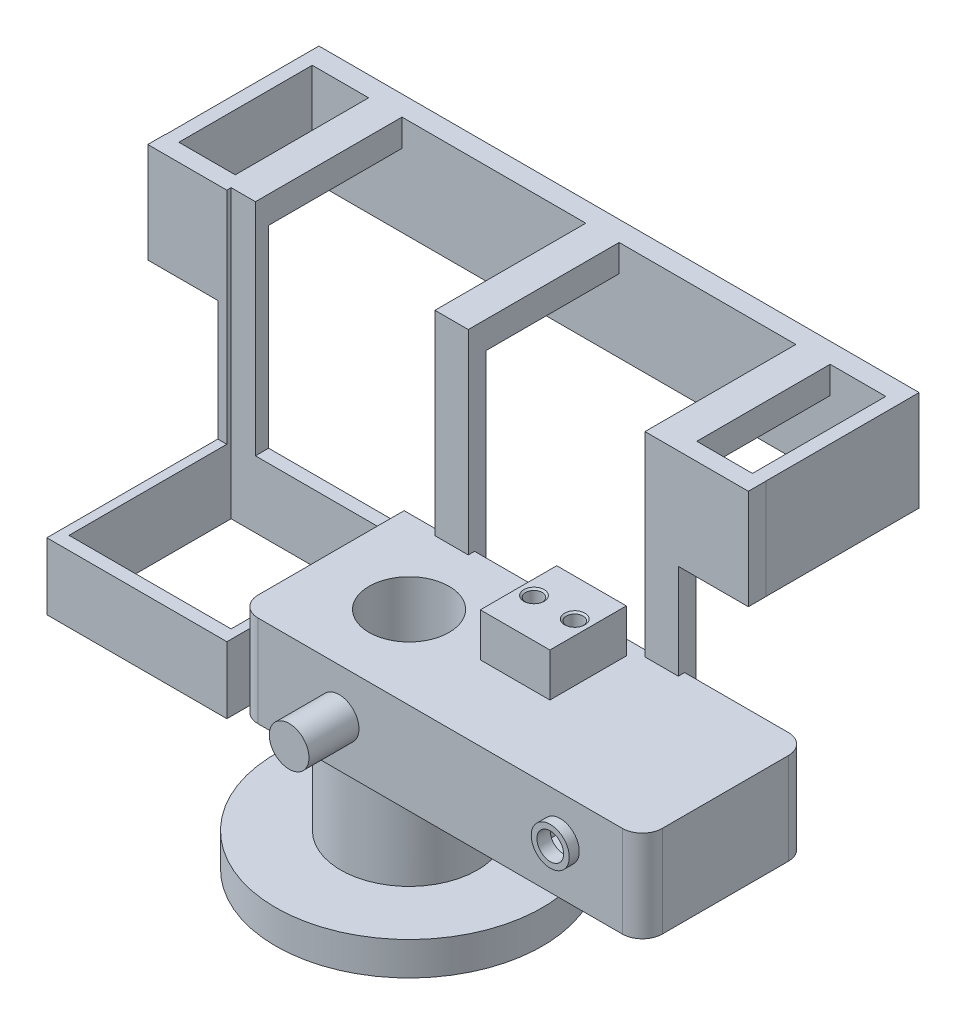
SolidWorks part; units mm, degrees
ref_plane "前基準面" through (0, 0, 0) normal (0, 0, 1) x (1, 0, 0)
ref_plane "上基準面" through (0, 0, 0) normal (0, 1, 0) x (1, 0, 0)
ref_plane "右基準面" through (0, 0, 0) normal (1, 0, 0) x (0, 0, -1)
sketch "草圖1" plane through (0, 0, 0) normal (0, 1, 0) x (1, 0, 0)
  line L1 (-30.3038, 12.448) -> (30.3038, 12.448)
  line L2 (-30.3038, 12.448) -> (-30.3038, -12.448)
  line L3 (-30.3038, -12.448) -> (30.3038, -12.448)
  line L4 (30.3038, 12.448) -> (30.3038, -12.448)
  line L5 (-30.3038, 12.448) -> (30.3038, -12.448) construction
  line L6 (-30.3038, -12.448) -> (30.3038, 12.448) construction
  point P0 (0, 0)
extrude "填料-伸長1" add sketch "草圖1" along normal blind 13.7304
sketch "草圖2" plane through (0, 0, 12.448) normal (0, 0, 1) x (1, 0, 0)
  line L6 (11.75, 12.75) -> (24.25, 12.75)
  line L7 (11.75, 12.75) -> (11.75, 2.25)
  line L8 (11.75, 2.25) -> (24.25, 2.25)
  line L9 (24.25, 12.75) -> (24.25, 2.25)
  line L10 (11.75, 12.75) -> (24.25, 2.25) construction
  line L11 (11.75, 2.25) -> (24.25, 12.75) construction
  point P10 (18, 7.5)
  dimension "D1" = 10.5
  dimension "D2" = 12.5
extrude "除料-伸長1" cut sketch "草圖2" against normal through all
sketch "草圖3" plane through (0, 0, 12.448) normal (0, 0, 1) x (1, 0, 0)
  line L0 (24.25, 2.25) -> (24.25, 12.75) construction
  line L1 (11.75, 12.75) -> (24.25, 12.75)
  line L2 (11.75, 12.75) -> (11.75, 2.25)
  line L3 (11.75, 2.25) -> (24.25, 2.25)
  line L4 (24.25, 12.75) -> (24.25, 2.25)
  line L5 (11.75, 12.75) -> (24.25, 2.25) construction
  line L6 (11.75, 2.25) -> (24.25, 12.75) construction
  line L7 (11.75, 2.25) -> (24.25, 2.25) construction
  point P0 (18, 7.5)
extrude "填料-伸長2" add sketch "草圖3" against normal blind 0.5
sketch "草圖4" plane through (0, 0, 11.948) normal (0, 0, -1) x (-1, 0, 0)
  circle A0 centre (-18, 7.5) radius 2
extrude "除料-伸長2" cut sketch "草圖4" against normal through all
sketch "草圖5" plane through (0, 0, 12.448) normal (0, 0, 1) x (1, 0, 0)
  circle A0 centre (-15.1519, 6.9) radius 2.975
extrude "填料-伸長3" add sketch "草圖5" along normal blind 7.5
sketch "草圖10" plane through (0, 13.7304, 0) normal (0, 1, 0) x (1, 0, 0)
  line L5 (-5.2158, 10.2392) -> (5.2158, 10.2392)
  line L6 (-5.2158, 10.2392) -> (-5.2158, -1.2175)
  line L7 (-5.2158, -1.2175) -> (5.2158, -1.2175)
  line L8 (5.2158, 10.2392) -> (5.2158, -1.2175)
  line L9 (-5.2158, 10.2392) -> (5.2158, -1.2175) construction
  line L10 (-5.2158, -1.2175) -> (5.2158, 10.2392) construction
  point P0 (0, 4.5109)
extrude "填料-伸長4" add sketch "草圖10" along normal blind 6.5
sketch "草圖14" plane through (0, 0, 12.448) normal (0, 0, 1) x (1, 0, 0)
  circle A0 centre (18, 7.5) radius 2.8505
  circle A1 centre (18, 7.5) radius 2
extrude "填料-伸長5" add sketch "草圖14" along normal blind 1.5
fillet "圓角2" radius 3 1 edges at (-30.3038, 6.8652, 12.448)
fillet "圓角3" radius 3 1 edges at (30.3038, 6.8652, -12.448)
fillet "圓角4" radius 3 1 edges at (30.3038, 6.8652, 12.448)
sketch "草圖16" plane through (0, 0, 0) normal (0, -1, 0) x (1, 0, 0)
  circle A0 centre (-17.1174, 0) radius 5.5
  circle A1 centre (-17.1174, 0) radius 7.5
extrude "填料-伸長6" add sketch "草圖16" along normal blind 15
sketch "草圖17" plane through (0, -15, 0) normal (0, -1, 0) x (1, 0, 0)
  circle A0 centre (-17.1174, 0) radius 9.15
  circle A1 centre (-17.1174, 0) radius 17.05
extrude "填料-伸長7" add sketch "草圖17" along normal blind 5 separate body
sketch "草圖18" plane through (0, -15, 0) normal (0, 1, 0) x (1, 0, 0)
  circle A0 centre (-17.1174, 0) radius 10.2514
extrude "填料-伸長8" add sketch "草圖18" along normal blind 15
sketch "草圖19" plane through (0, -15, 0) normal (0, -1, 0) x (1, 0, 0)
  circle A0 centre (-17.1174, 0) radius 6
extrude "除料-伸長3" cut sketch "草圖19" against normal through all
sketch "草圖20" plane through (0, -20, 0) normal (0, -1, 0) x (1, 0, 0)
  line L1 (-27.7874, 1.565) -> (-27.7874, -1.565)
  line L2 (-27.7874, 1.565) -> (-26.1326, 1.565)
  line L3 (-27.7874, -1.565) -> (-26.1326, -1.565)
  line L4 (-26.1326, 1.565) -> (-26.1326, -1.565)
  circle A0 centre (-17.1174, 0) radius 9.15 construction
  point P7 (-27.7874, 0)
extrude "除料-伸長4" cut sketch "草圖20" against normal blind 15
sketch "草圖21" plane through (0, -15, 0) normal (0, -1, 0) x (1, 0, 0)
  line L0 (-26.1326, 1.565) -> (-25.7373, 1.565)
  line L1 (-26.1326, -1.565) -> (-25.7373, -1.565)
  line L2 (-25.7373, -1.565) -> (-25.7373, 1.565)
  line L3 (-26.1326, 1.565) -> (-26.1326, -1.565)
extrude "除料-伸長5" cut sketch "草圖21" against normal blind 10
sketch "草圖22" plane through (0, -15, 0) normal (0, 1, 0) x (1, 0, 0)
  circle A0 centre (-17.1174, 0) radius 19.9648
extrude "除料-伸長6" cut sketch "草圖22" against normal blind 10
sketch "草圖47" plane through (0, -15, 0) normal (0, -1, 0) x (1, 0, 0)
  circle A0 centre (-17.1174, 0) radius 20
extrude "填料-伸長16" add sketch "草圖47" along normal blind 5
sketch "草圖48" plane through (0, -15, 0) normal (0, 1, 0) x (1, 0, 0)
  circle A0 centre (-17.1174, 0) radius 6
extrude "除料-伸長21" cut sketch "草圖48" against normal blind 5
sketch "草圖49" plane through (0, -20, 0) normal (0, -1, 0) x (1, 0, 0)
  circle A0 centre (-17.1174, 0) radius 17.3
  circle A1 centre (-17.1174, 0) radius 14.8
extrude "除料-伸長22" cut sketch "草圖49" against normal blind 3
sketch "草圖50" plane through (0, -20, 0) normal (0, -1, 0) x (1, 0, 0)
  circle A0 centre (-17.1174, 0) radius 18.5909
  arc A1 (-2.1064, 10.9677) -> (0.2479, 6.6384) centre (-17.1174, 0) cw
  circle A2 centre (-17.1174, 0) radius 8.4841
sketch "草圖51" plane through (0, -20, 0) normal (0, -1, 0) x (1, 0, 0)
  line L0 (-3.1487, 10.2061) -> (-2.1064, 10.9677)
  line L1 (-0.958, 6.1775) -> (0.2479, 6.6384)
  line L2 (-15.2631, -17.2003) -> (-15.1247, -18.4838)
  line L3 (-19.8473, -17.0833) -> (-20.051, -18.358)
  line L4 (-32.9405, 6.9942) -> (-34.1213, 7.5161)
  line L5 (-30.547, 10.9058) -> (-31.5491, 11.7196)
  arc A0 (-3.1487, 10.2061) -> (-0.958, 6.1775) centre (-17.1174, 0) cw
  circle A1 centre (-17.1174, 0) radius 17.3 construction
  arc A2 (-15.1247, -18.4838) -> (-20.051, -18.358) centre (-17.1174, 0) cw
  arc A3 (-2.1064, 10.9677) -> (0.2479, 6.6384) centre (-17.1174, 0) cw
  arc A4 (-15.2631, -17.2003) -> (-19.8473, -17.0833) centre (-17.1174, 0) cw
  arc A5 (-34.1213, 7.5161) -> (-31.5491, 11.7196) centre (-17.1174, 0) cw
  arc A6 (-32.9405, 6.9942) -> (-30.547, 10.9058) centre (-17.1174, 0) cw
  point P23 (-17.1174, 0)
  dimension "D1" = 3
extrude "除料-伸長23" cut sketch "草圖51" against normal blind 3
sketch "草圖52" plane through (0, -17, 0) normal (0, -1, 0) x (1, 0, 0)
  circle A0 centre (-17.1174, 0) radius 18.5909
extrude "除料-伸長24" cut sketch "草圖52" along normal blind 2.3
sketch "草圖43" plane through (0, 0, 0) normal (0, -1, 0) x (1, 0, 0)
  line L0 (-30.3038, 14.126) -> (-30.3038, -14.126)
  line L1 (-57.3038, -14.126) -> (-57.3038, 14.126)
  line L2 (-30.3038, -14.126) -> (-57.3038, -14.126)
  line L3 (-57.3038, 14.126) -> (-30.3038, 14.126)
  line L6 (-55.9538, 12.15) -> (-31.6538, 12.15)
  line L7 (-55.9538, 12.15) -> (-55.9538, -12.15)
  line L8 (-55.9538, -12.15) -> (-31.6538, -12.15)
  line L9 (-31.6538, 12.15) -> (-31.6538, -12.15)
  line L10 (-55.9538, 12.15) -> (-31.6538, -12.15) construction
  line L11 (-55.9538, -12.15) -> (-31.6538, 12.15) construction
  point P3 (-30.3038, 0)
  point P7 (-43.8038, 0)
  dimension "D1" = 27
  dimension "D2" = 24.3
  dimension "D3" = 24.3
extrude "填料-伸長14" add sketch "草圖43" against normal blind 10
sketch "草圖53" plane through (0, -20, 0) normal (0, -1, 0) x (1, 0, 0)
  line L0 (-21.4684, 18.0746) -> (-18.5217, 5.8334)
  line L1 (-12.8881, 18.1034) -> (-15.7525, 5.8427)
  line L2 (0.7111, -5.2692) -> (-11.3635, -1.7006)
  line L3 (-3.5541, -12.7145) -> (-12.74, -4.1034)
  line L4 (-30.595, -12.8054) -> (-21.4672, -4.1328)
  line L5 (-34.9102, -5.389) -> (-22.8598, -1.7392)
  circle A1 centre (-17.1174, 0) radius 18.5909 construction
  circle A2 centre (-17.1174, 0) radius 6 construction
  arc A3 (-15.7525, 5.8427) -> (-18.5217, 5.8334) centre (-17.1174, 0) ccw
  arc A4 (-21.4684, 18.0746) -> (-12.8881, 18.1034) centre (-17.1174, 0) cw
  arc A5 (0.7111, -5.2692) -> (-3.5541, -12.7145) centre (-17.1174, 0) cw
  arc A6 (-12.74, -4.1034) -> (-11.3635, -1.7006) centre (-17.1174, 0) ccw
  arc A7 (-30.595, -12.8054) -> (-34.9102, -5.389) centre (-17.1174, 0) cw
  arc A8 (-22.8598, -1.7392) -> (-21.4672, -4.1328) centre (-17.1174, 0) ccw
  point P20 (-17.1174, 0)
  dimension "D1" = 3
extrude "填料-伸長17" add sketch "草圖53" against normal blind 5
sketch "草圖54" plane through (0, -20, 0) normal (0, -1, 0) x (1, 0, 0)
  circle A0 centre (-17.1174, 0) radius 14.8
  circle A1 centre (-17.1174, 0) radius 6
extrude "填料-伸長18" add sketch "草圖54" against normal blind 5
sketch "草圖56" plane through (30.3038, 0, 0) normal (1, 0, 0) x (0, 0, -1)
  line L0 (14.126, 10) -> (14.126, 0)
  line L1 (14.126, 0) -> (12.448, 0)
  line L2 (12.448, 0) -> (12.448, 10)
  line L3 (14.126, 10) -> (12.448, 10) construction
  line L4 (12.448, 10) -> (14.126, 10)
extrude "填料-伸長19" add sketch "草圖56" against normal blind 80
sketch "草圖57" plane through (0, 0, -12.448) normal (0, 0, -1) x (-1, 0, 0)
  line L0 (-24.25, 12.75) -> (-11.75, 12.75)
  line L1 (-11.75, 12.75) -> (-11.75, 0.75)
  line L2 (-24.25, 12.75) -> (-24.25, 0.75)
  line L3 (-24.25, 0.75) -> (-11.75, 0.75)
extrude "除料-伸長28" cut sketch "草圖57" along normal blind 80
sketch "草圖58" plane through (30.3038, 0, 0) normal (1, 0, 0) x (0, 0, -1)
  line L0 (12.448, 10) -> (14.126, 10)
  line L1 (14.126, 10) -> (14.126, 0)
  line L2 (14.126, 0) -> (12.448, 0)
  line L3 (12.448, 0) -> (12.448, 10)
extrude "除料-伸長29" cut sketch "草圖58" against normal blind 18.5
sketch "草圖59" plane through (0, 0, -14.126) normal (0, 0, -1) x (-1, 0, 0)
  line L0 (-11.75, 10) -> (-11.75, 43)
  line L1 (-11.75, 10) -> (-6.75, 10)
  line L2 (57.3038, 10) -> (-11.75, 10) construction
  line L3 (-6.75, 10) -> (-6.75, 43)
  line L4 (-6.75, 43) -> (-11.75, 43)
  line L5 (57.3038, 10) -> (57.3038, 43)
  line L6 (57.3038, 43) -> (52.3038, 43)
  line L7 (52.3038, 43) -> (52.3038, 0)
  line L8 (57.3038, 0) -> (-11.8038, 0) construction
  line L9 (52.3038, 0) -> (57.3038, 0)
  line L10 (19.7432, 0) -> (19.7432, 43)
  line L11 (19.7432, 43) -> (24.7432, 43)
  line L12 (24.7432, 43) -> (24.7432, 0)
  line L13 (24.7432, 0) -> (19.7432, 0)
  line M14 (57.3038, 10) -> (-11.75, 10)
  dimension "D1" = 5
  dimension "D2" = 5
  dimension "D3" = 5
extrude "填料-伸長21" add sketch "草圖59" against normal blind 2.621 contours L3 L4 L0 M14 | L12 L11 L10 M14 | L6 L7 L5 M14
sketch "草圖60" plane through (-57.3038, 0, 0) normal (-1, 0, 0) x (0, 0, 1)
  line L0 (-14.126, 43) -> (-39.126, 43)
  line L1 (-39.126, 43) -> (-39.126, 38.9382)
  line L3 (-11.5051, 10) -> (-11.5051, 43) construction
  line L4 (-39.126, 38.9382) -> (-14.126, 38.9382)
  line L5 (-14.126, 38.9382) -> (-14.126, 43)
  line L10 (-14.126, 0) -> (14.126, 0)
  line L11 (14.126, 0) -> (14.126, 10)
  line L12 (14.126, 10) -> (-11.5051, 10)
  line L13 (-11.5051, 10) -> (-11.5051, 43)
  line L14 (-11.5051, 43) -> (-14.126, 43)
  line L15 (-14.126, 43) -> (-14.126, 0)
  line L16 (-14.126, 0) -> (14.126, 0)
  line L17 (14.126, 0) -> (14.126, 10)
  line L18 (14.126, 10) -> (-11.5051, 10)
  line L19 (-11.5051, 10) -> (-11.5051, 38.9382)
  line L21 (-14.126, 43) -> (-14.126, 0)
  line M12 (-14.126, 43) -> (-14.126, 0)
  dimension "D1" = 0
extrude "填料-伸長22" add sketch "草圖60" against normal blind 69.2 contours L1 L4 L0 M12
sketch "草圖61" plane through (0, 43, 0) normal (0, 1, 0) x (1, 0, 0)
  line L0 (6.75, 14.126) -> (6.75, 34.126)
  line L1 (-19.7432, 14.126) -> (-19.7432, 34.126)
  line L2 (-19.7432, 34.126) -> (6.75, 34.126)
  line L3 (-24.7432, 14.126) -> (-24.7432, 34.126)
  line L4 (-52.3038, 14.126) -> (-52.3038, 34.126)
  line L5 (-52.3038, 34.126) -> (-24.7432, 34.126)
  line L6 (-52.3038, 14.126) -> (-24.7432, 14.126)
  line L7 (-19.7432, 14.126) -> (6.75, 14.126)
extrude "除料-伸長30" cut sketch "草圖61" against normal blind 5.2
sketch "草圖62" plane through (0, 38.9382, 0) normal (0, -1, 0) x (1, 0, 0)
  line L0 (-57.3038, -39.126) -> (11.8962, -39.126)
  line L1 (-52.3038, -34.126) -> (11.8962, -34.126)
  line L2 (11.8962, -39.126) -> (11.8962, -14.126) construction
  line L3 (11.8962, -34.126) -> (11.8962, -39.126)
  line L4 (-57.3038, -39.126) -> (-57.3038, -34.126)
  line L5 (-57.3038, -39.126) -> (-57.3038, -14.126) construction
  line L6 (-57.3038, -34.126) -> (-52.3038, -34.126)
sketch "草圖68" plane through (0, 0, -34.126) normal (0, 0, 1) x (1, 0, 0)
  line L0 (-65.7613, 43) -> (20.2387, 43)
  line L2 (20.2387, 43) -> (20.2387, 28)
  line L3 (20.2387, 28) -> (-65.7613, 28)
  line L4 (-65.7613, 28) -> (-65.7613, 43)
  point P3 (-22.7613, 43)
  dimension "D1" = 86
extrude "填料-伸長25" add sketch "草圖68" against normal blind 3
sketch "草圖69" plane through (0, 0, -39.126) normal (0, 0, -1) x (-1, 0, 0)
  line L0 (-11.8962, 43) -> (-11.8962, 38.9382)
  line L1 (-11.8962, 38.9382) -> (57.3038, 38.9382)
  line L2 (57.3038, 38.9382) -> (57.3038, 43)
  line L3 (57.3038, 43) -> (-11.8962, 43)
extrude "除料-伸長34" cut sketch "草圖69" against normal blind 2
sketch "草圖70" plane through (20.2387, 0, 0) normal (1, 0, 0) x (0, 0, -1)
  line L0 (37.126, 28) -> (37.126, 43)
  line L1 (37.126, 43) -> (14.126, 43)
  line L2 (14.126, 43) -> (14.126, 28)
  line L3 (14.126, 38.9382) -> (14.126, 0.75) construction
  line L4 (14.126, 28) -> (37.126, 28)
extrude "填料-伸長27" add sketch "草圖70" along normal blind 2
sketch "草圖71" plane through (-65.7613, 0, 0) normal (-1, 0, 0) x (0, 0, 1)
  line L0 (-37.126, 28) -> (-14.126, 28)
  line L1 (-14.126, 28) -> (-14.126, 43)
  line L2 (-11.5051, 43) -> (-34.126, 43) construction
  line L3 (-14.126, 43) -> (-14.126, 28) construction
  line L4 (-14.126, 43) -> (-37.126, 43)
  line L5 (-37.126, 43) -> (-37.126, 28)
extrude "填料-伸長28" add sketch "草圖71" along normal blind 2
sketch "草圖72" plane through (-57.3038, 0, 0) normal (-1, 0, 0) x (0, 0, 1)
  line L0 (-14.126, 43) -> (-11.5051, 43)
  line L1 (-11.5051, 43) -> (-11.5051, 27.998)
  line L2 (-11.5051, 10) -> (-11.5051, 43) construction
  line L3 (-11.5051, 27.998) -> (-14.126, 28)
  line L4 (-14.126, 28) -> (-14.126, 43)
extrude "填料-伸長29" add sketch "草圖72" along normal blind 10.5
sketch "草圖73" plane through (11.75, 0, 0) normal (1, 0, 0) x (0, 0, -1)
  line L0 (11.5051, 27.998) -> (14.126, 28)
  line L1 (14.126, 28) -> (14.126, 43)
  line L2 (14.126, 43) -> (11.5051, 43)
  line L3 (11.5051, 43) -> (11.5051, 27.998)
extrude "填料-伸長30" add sketch "草圖73" along normal blind 10.5
sketch "草圖74" plane through (0, 10, 0) normal (0, -1, 0) x (1, 0, 0)
  line L0 (-52.3038, -11.5051) -> (-55.9538, -11.5051)
  line L1 (-55.9538, -11.5051) -> (-55.9538, -12.15)
  line L2 (-55.9538, -12.15) -> (-52.3038, -12.15)
  line L3 (-52.3038, -12.15) -> (-52.3038, -11.5051)
extrude "除料-伸長35" cut sketch "草圖74" against normal through all
sketch "草圖76" plane through (0, 20.2304, 0) normal (0, 1, 0) x (1, 0, 0)
  line L0 (-3.0568, 4.6706) -> (3.0568, 4.6706)
  point P1 (3.0568, 4.6706)
  point P2 (-3.0568, 4.6706)
  point P3 (0, 4.6706)
hole_wizard "M3 螺紋孔1" positions "草圖80" profile "草圖82" tap size "M3" standard "ISO"
sketch "草圖80" plane through (0, 20.2304, 0) normal (0, 1, 0) x (1, 0, 0)
  point P0 (-3.0568, 4.6706)
  point P3 (3.0568, 4.6706)
sketch "草圖82" plane through (-3.0568, 20.2304, -4.6706) normal (1, 0, 0) x (0, 0, 1)
  line L0 (0, 0) -> (0, 15.7511)
  line L1 (0, 15.7511) -> (1.25, 15)
  line L2 (1.25, 15) -> (1.25, 0.2308)
  line L3 (1.25, 0.2308) -> (1.525, 0)
  line L5 (1.525, 0) -> (0, 0)
  line L6 (-1.25, 0.2308) -> (-1.525, 0) construction
  line L10 (0, 15.7511) -> (-1.25, 15) construction
  line L11 (0, -6.35) -> (0, 107.95) construction
  dimension "螺孔鑽直徑" = 2.5
  dimension "螺孔鑽深度" = 15
  dimension "近端錐孔直徑" = 3.05
  dimension "近端錐孔角度" = 100
  dimension "導頭角度" = 118
cosmetic thread "鑽孔螺紋1" parameters "D1"=2.7, "D2"=3
cosmetic thread "鑽孔螺紋2" parameters "D1"=2.7, "D2"=3
